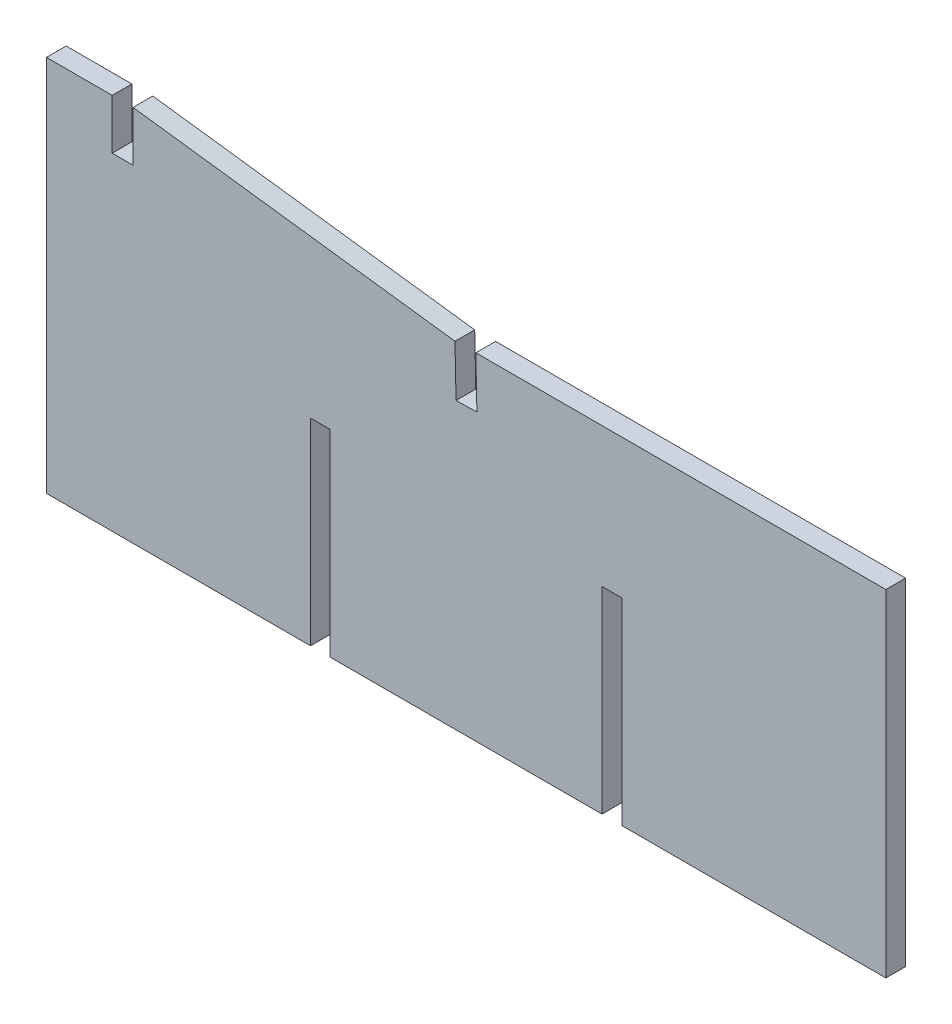
SolidWorks part; units mm, degrees
ref_plane "Front Plane" through (0, 0, 0) normal (0, 0, 1) x (1, 0, 0)
ref_plane "Top Plane" through (0, 0, 0) normal (0, 1, 0) x (1, 0, 0)
ref_plane "Right Plane" through (0, 0, 0) normal (1, 0, 0) x (0, 0, -1)
ref_plane "Plane1" through (0, 0, -196) normal (0, 0, 1) x (1, 0, 0)
sketch "Sketch1" plane through (0, 0, -196) normal (0, 0, 1) x (1, 0, 0)
  line L0 (266.6765, 83.2463) -> (266.6765, 75.6256)
  line L1 (269.8515, 83.2463) -> (269.8515, 75.6256)
  line L2 (266.6765, 75.6256) -> (269.8515, 75.6256)
  line L3 (266.6765, 83.2463) -> (269.8515, 83.2463)
  line L5 (266.6765, 75.6256) -> (269.8515, 75.6256)
  line L6 (269.8515, 83.2463) -> (269.8515, 75.6256)
  line L7 (266.6765, 83.2463) -> (266.6765, 75.6256)
  line L8 (322.0015, 76.9918) -> (322.1615, 69.2692)
  line L9 (318.8272, 76.9256) -> (318.9872, 69.203)
  line L10 (318.9872, 69.203) -> (322.1615, 69.2692)
  line L11 (322.0015, 76.9918) -> (318.8272, 76.9256)
  line L13 (318.9872, 69.203) -> (322.1615, 69.2692)
  line L14 (318.8272, 76.9256) -> (318.9872, 69.203)
  line L15 (322.0015, 76.9918) -> (322.1615, 69.2692)
  line L16 (269.8515, 83.2463) -> (318.8272, 76.9256)
  line L17 (322.0015, 76.9918) -> (384.3725, 76.9918)
  line L18 (384.3725, 76.9918) -> (384.3725, 25.8076)
  line L19 (384.3725, 25.8076) -> (344.1975, 25.8076)
  line L20 (256.6765, 25.8076) -> (256.6765, 83.2463)
  line L21 (256.6765, 83.2463) -> (266.6765, 83.2463)
  line L23 (374.3725, 75.768) -> (374.3725, 79.591) construction
  line L24 (296.8515, 25.8076) -> (296.8515, 55.8076)
  line L25 (296.8515, 55.8076) -> (299.8515, 55.8076)
  line L26 (299.8515, 55.8076) -> (299.8515, 25.8076)
  line L27 (341.1975, 25.8076) -> (341.1975, 55.8076)
  line L28 (341.1975, 55.8076) -> (344.1975, 55.8076)
  line L29 (344.1975, 55.8076) -> (344.1975, 25.8076)
  line L30 (371.1975, 71.9705) -> (371.1975, 41.4065) construction
  line L31 (269.8515, 57.5419) -> (269.8515, 63.8179) construction
  line L32 (296.8515, 25.8076) -> (256.6765, 25.8076)
  line L33 (341.1975, 25.8076) -> (299.8515, 25.8076)
  dimension "D1" = 10
  dimension "D2" = 10
  dimension "D3" = 3
  dimension "D4" = 30
  dimension "D5" = 30
  dimension "D6" = 3
  dimension "D7" = 30
  dimension "D8" = 30
extrude "Boss-Extrude1" add sketch "Sketch1" along normal blind 3
